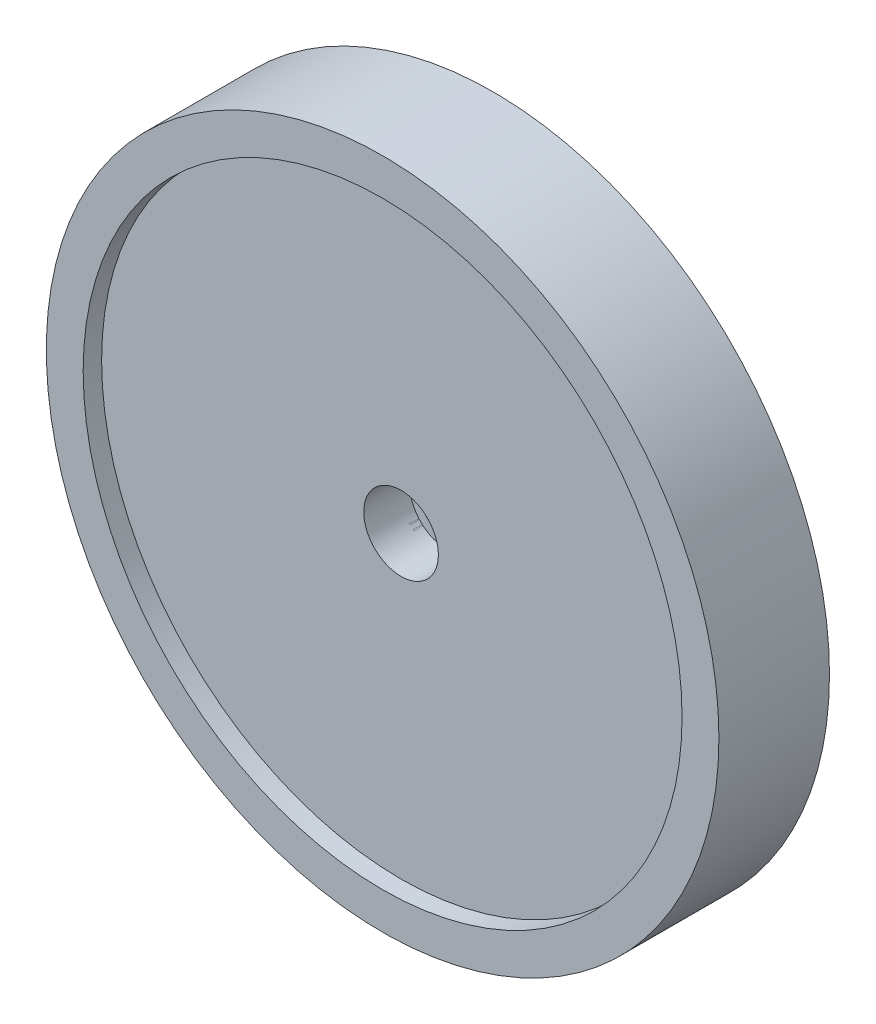
SolidWorks part; units mm, degrees
ref_plane "Alzado" through (0, 0, 0) normal (0, 0, 1) x (1, 0, 0)
ref_plane "Planta" through (0, 0, 0) normal (0, 1, 0) x (1, 0, 0)
ref_plane "Vista lateral" through (0, 0, 0) normal (1, 0, 0) x (0, 0, -1)
sketch "Croquis1" plane through (0, 0, 0) normal (0, 0, 1) x (1, 0, 0)
  circle A0 centre (0, 0) radius 36.5
  dimension "D1" = 73
extrude "Saliente-Extruir1" add sketch "Croquis1" along normal mid plane 12
sketch "Croquis3" plane through (0, 0, 6) normal (0, 0, 1) x (1, 0, 0)
  circle A0 centre (0, 0) radius 32.5
  dimension "D1" = 65
extrude "Cortar-Extruir2" cut sketch "Croquis3" against normal blind 2
sketch "Croquis4" plane through (0, 0, -6) normal (0, 0, -1) x (-1, 0, 0)
  circle A0 centre (0, 0) radius 32.5
  dimension "D1" = 65
extrude "Cortar-Extruir3" cut sketch "Croquis4" against normal blind 5
sketch "Croquis5" plane through (0, 0, 0) normal (1, 0, 0) x (0, 0, -1)
  line L0 (12.655, 0) -> (0, -15.4871)
  line L1 (0, -15.4871) -> (0, 15.4871)
  line L2 (0, 15.4871) -> (12.655, 0)
  line L3 (6.6, 0) -> (-6.6, 0) construction
  dimension "D1" = 20
  dimension "D2" = 20
extrude "Saliente-Extruir2" add sketch "Croquis5" along normal mid plane 1
sketch "Croquis6" plane through (0, 0, 0) normal (0, 1, 0) x (1, 0, 0)
  line L0 (0, 12.655) -> (-15.4871, 0)
  line L1 (0.5, 12.655) -> (-0.5, 12.655) construction
  line L2 (-15.4871, 0) -> (15.4871, 0)
  line L3 (15.4871, 0) -> (0, 12.655)
  dimension "D1" = 20
  dimension "D2" = 20
extrude "Saliente-Extruir3" add sketch "Croquis6" along normal mid plane 1
sketch "Croquis8" plane through (0, 0, 4) normal (0, 0, 1) x (1, 0, 0)
  line L0 (0, 0) -> (-18.6676, 18.6676) construction
  line L2 (0, -10.2366) -> (0, 10.2366) construction
  dimension "D1" = 45
ref_plane "Plano1" through (0, 0, 4) normal (-0.7071, 0.7071, 0) x (0, 0, 1)
sketch "Croquis10" plane through (0, 0, 4) normal (-0.7071, 0.7071, 0) x (0, 0, 1)
  line L0 (-4, -15.6573) -> (-16.6121, -0.1352)
  line L1 (-16.6121, -0.1352) -> (-4, 15.3869)
  line L2 (-4, 15.3869) -> (-4, -15.6573)
  line L3 (-4, -40.15) -> (-4, 40.15) construction
  dimension "D1" = 20
  dimension "D2" = 20
extrude "Saliente-Extruir7" add sketch "Croquis10" along normal mid plane 1 separate body
sketch "Croquis11" plane through (0, 0, -1) normal (0, 0, -1) x (-1, 0, 0)
  line L0 (0, 0) -> (21.0537, -21.0537) construction
  line L1 (10.2672, -10.2672) -> (-10.2672, 10.2672) construction
  line L2 (10.2366, 0) -> (-10.2366, 0) construction
  dimension "D1" = 45
ref_plane "Plano2" through (0, 0, 4) normal (-0.7071, -0.7071, 0) x (-0.7071, 0.7071, 0)
sketch "Croquis14" plane through (0, 0, 4) normal (-0.7071, -0.7071, 0) x (-0.7071, 0.7071, 0)
  line L0 (-15.5221, 4) -> (0, 16.6121)
  line L1 (0, 16.6121) -> (15.5221, 4)
  line L2 (15.5221, 4) -> (-15.5221, 4)
  line L4 (0.5, 16.6121) -> (-0.5, 16.6121) construction
  point P2 (0, 4)
  dimension "D1" = 20
  dimension "D2" = 20
extrude "Saliente-Extruir8" add sketch "Croquis14" along normal mid plane 1 separate body
sketch "Croquis2" plane through (0, 0, -6) normal (0, 0, -1) x (-1, 0, 0)
  circle A0 centre (0, 0) radius 4.05
  dimension "D1" = 8.1
sketch "Croquis7" plane through (0, 0, -1) normal (0, 0, -1) x (-1, 0, 0)
  circle A0 centre (0, 0) radius 4.05
  circle A1 centre (0, 0) radius 3.05
  dimension "D1" = 8.1
  dimension "D2" = 6.1
extrude "Cortar-Extruir4" cut sketch "Croquis2" against normal blind 62 and the other way blind 68
extrude "Saliente-Extruir10" add sketch "Croquis7" along normal up to vertex (8.3456 mm away) separate body
